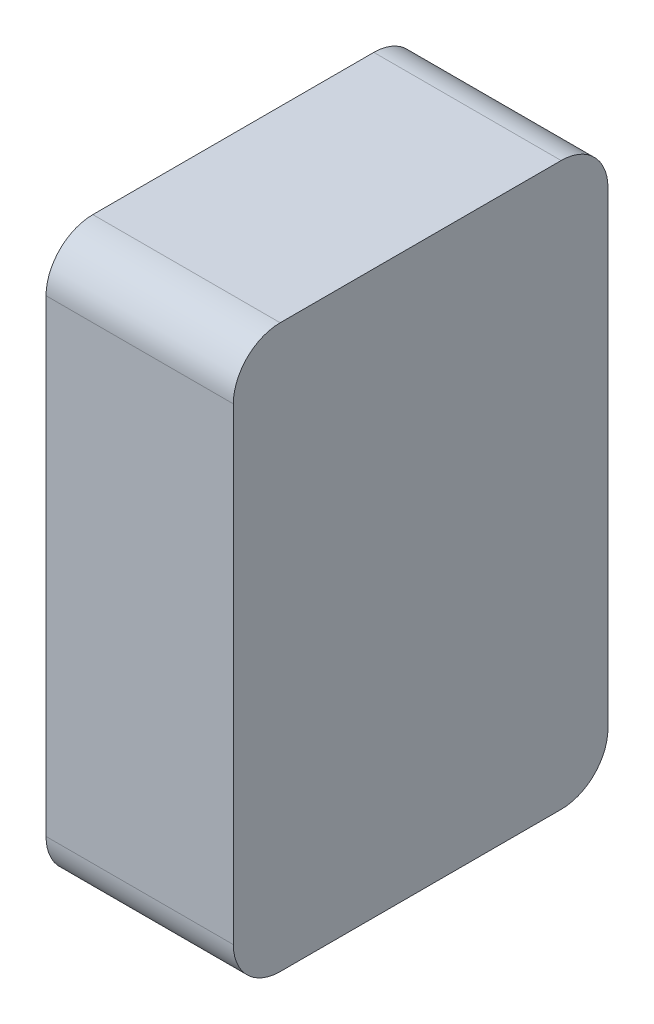
SolidWorks part; units mm, degrees
material "7075-T6 (SN)"
ref_plane "Front Plane" through (0, 0, 0) normal (0, 0, 1) x (1, 0, 0)
ref_plane "Top Plane" through (0, 0, 0) normal (0, 1, 0) x (1, 0, 0)
ref_plane "Right Plane" through (0, 0, 0) normal (1, 0, 0) x (0, 0, -1)
sketch "Sketch2" plane through (0, 0, 0) normal (1, 0, 0) x (0, 0, -1)
  line L0 (-60, 60) -> (-60, 120)
  line L1 (-60, 60) -> (60, 60) construction
  line L2 (-60, 60) -> (-60, -60)
  line L3 (-60, -60) -> (60, -60)
  line L4 (60, 60) -> (60, -60)
  line L5 (-60, 120) -> (60, 120)
  line L6 (60, 120) -> (60, 60)
  point P4 (0, 60)
  point P9 (-60, 0)
  dimension "D1" = 120
  dimension "D2" = 60
extrude "Boss-Extrude1" add sketch "Sketch2" along normal blind 60
sketch "Sketch3" plane through (0, 0, 0) normal (-1, 0, 0) x (0, 0, 1)
  circle A0 centre (0, 0) radius 45
  dimension "D1" = 90
extrude "Cut-Extrude1" cut sketch "Sketch3" against normal blind 40
fillet "Fillet1" radius 15 4 edges at (30, 120, -60) (30, 120, 60) (30, -60, 60) (30, -60, -60)
